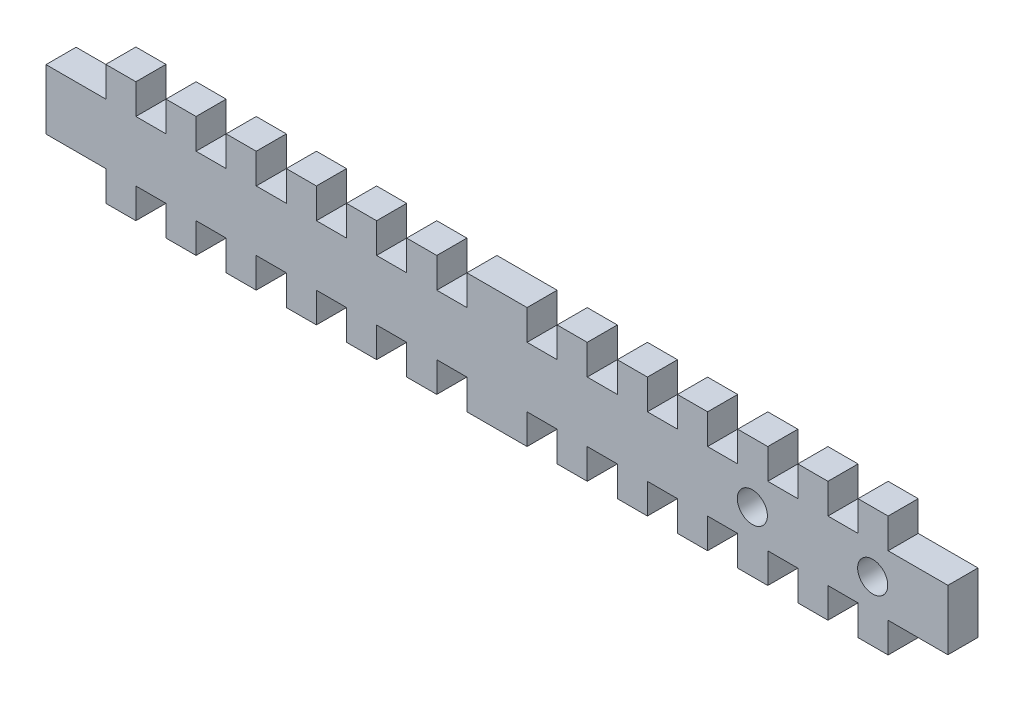
SolidWorks part; units mm, degrees
ref_plane "Front Plane" through (0, 0, 0) normal (0, 0, 1) x (1, 0, 0)
ref_plane "Top Plane" through (0, 0, 0) normal (0, 1, 0) x (1, 0, 0)
ref_plane "Right Plane" through (0, 0, 0) normal (1, 0, 0) x (0, 0, -1)
sketch "Sketch1" plane through (0, 0, 0) normal (0, 0, 1) x (1, 0, 0)
  line L0 (-95.25, 21.2167) -> (-82.55, 21.2167) construction
  line L1 (-82.55, 12.7) -> (-76.2, 12.7)
  line L2 (-95.1675, 6.35) -> (-95.1675, -6.35)
  line L3 (-82.55, -12.7) -> (-76.2, -12.7)
  line L4 (95.1675, 6.35) -> (95.1675, -6.35)
  line L5 (-95.25, 12.7) -> (95.25, -12.7) construction
  line L6 (-95.25, -12.7) -> (95.25, 12.7) construction
  line L7 (-82.55, 12.7) -> (-82.55, 6.35)
  line L8 (-82.55, 6.35) -> (-95.1675, 6.35)
  line L9 (0, 2.9169) -> (0, -2.0983) construction
  line L10 (-3.425, 0) -> (5.9529, 0) construction
  line L11 (-82.55, -6.35) -> (-95.1675, -6.35)
  line L12 (-82.55, -12.7) -> (-82.55, -6.35)
  line L13 (82.55, -12.7) -> (82.55, -6.35)
  line L14 (82.55, -6.35) -> (95.1675, -6.35)
  line L15 (82.55, 12.7) -> (82.55, 6.35)
  line L16 (82.55, 6.35) -> (95.1675, 6.35)
  line L17 (-82.55, -20.0623) -> (-76.2, -20.0623) construction
  line L18 (-76.2, -12.7) -> (-76.2, -6.35)
  line L19 (-69.85, 12.7) -> (-63.5, 12.7)
  line L20 (-57.15, 12.7) -> (-50.8, 12.7)
  line L21 (-76.2, 12.7) -> (-76.2, 6.35)
  line L22 (-63.5, 12.7) -> (-63.5, 6.35)
  line L23 (-69.85, 12.7) -> (-69.85, 6.35)
  line L24 (-50.8, 6.35) -> (-44.45, 6.35)
  line L25 (-50.8, 12.7) -> (-50.8, 6.35)
  line L26 (-57.15, 12.7) -> (-57.15, 6.35)
  line L27 (-38.1, 6.35) -> (-31.75, 6.35)
  line L28 (-38.1, 12.7) -> (-38.1, 6.35)
  line L29 (-44.45, 12.7) -> (-44.45, 6.35)
  line L30 (-25.4, 6.35) -> (-19.05, 6.35)
  line L31 (-25.4, 12.7) -> (-25.4, 6.35)
  line L32 (-31.75, 12.7) -> (-31.75, 6.35)
  line L33 (-12.7, 6.35) -> (-6.35, 6.35)
  line L34 (-12.7, 12.7) -> (-12.7, 6.35)
  line L35 (-19.05, 12.7) -> (-19.05, 6.35)
  line L36 (12.7, -6.35) -> (6.35, -6.35)
  line L37 (6.35, 12.7) -> (0, 12.7)
  line L38 (-6.35, 12.7) -> (-6.35, 6.35)
  line L39 (-6.35, -6.35) -> (-12.7, -6.35)
  line L40 (12.7, 12.7) -> (12.7, 6.35)
  line L41 (6.35, 12.7) -> (6.35, 6.35)
  line L42 (6.35, 6.35) -> (12.7, 6.35)
  line L43 (25.4, 12.7) -> (25.4, 6.35)
  line L44 (19.05, 12.7) -> (19.05, 6.35)
  line L45 (19.05, 6.35) -> (25.4, 6.35)
  line L46 (38.1, 12.7) -> (38.1, 6.35)
  line L47 (31.75, 12.7) -> (31.75, 6.35)
  line L48 (82.55, 6.35) -> (82.55, 12.7)
  line L49 (31.75, 6.35) -> (38.1, 6.35)
  line L50 (50.8, 12.7) -> (50.8, 6.35)
  line L51 (44.45, 12.7) -> (44.45, 6.35)
  line L52 (44.45, 6.35) -> (50.8, 6.35)
  line L53 (63.5, 12.7) -> (63.5, 6.35)
  line L54 (57.15, 12.7) -> (57.15, 6.35)
  line L55 (57.15, 6.35) -> (63.5, 6.35)
  line L56 (-19.05, 12.7) -> (-12.7, 12.7)
  line L57 (6.35, 12.7) -> (-6.35, 12.7)
  line L58 (76.2, 12.7) -> (76.2, 6.35)
  line L59 (-12.7, 12.7) -> (-19.05, 12.7)
  line L60 (-25.4, 12.7) -> (-31.75, 12.7)
  line L61 (-38.1, 12.7) -> (-44.45, 12.7)
  line L62 (31.75, 12.7) -> (25.4, 12.7)
  line L63 (44.45, 12.7) -> (38.1, 12.7)
  line L64 (57.15, 12.7) -> (50.8, 12.7)
  line L65 (69.85, 12.7) -> (63.5, 12.7)
  line L66 (69.85, 12.7) -> (69.85, 6.35)
  line L67 (69.85, 6.35) -> (76.2, 6.35)
  line L68 (-44.45, -6.35) -> (-50.8, -6.35)
  line L69 (-69.85, -12.7) -> (-69.85, -6.35)
  line L70 (-63.5, -12.7) -> (-63.5, -6.35)
  line L71 (-31.75, -6.35) -> (-38.1, -6.35)
  line L72 (-57.15, -12.7) -> (-57.15, -6.35)
  line L73 (-50.8, -12.7) -> (-50.8, -6.35)
  line L74 (95.1675, 0) -> (79.2925, 0) construction
  line L75 (79.2925, 0) -> (53.8925, 0) construction
  line L80 (-19.05, -6.35) -> (-25.4, -6.35)
  line L81 (-44.45, -12.7) -> (-44.45, -6.35)
  line L82 (-38.1, -12.7) -> (-38.1, -6.35)
  line L83 (-63.5, 6.35) -> (-57.15, 6.35)
  line L84 (-31.75, -12.7) -> (-31.75, -6.35)
  line L85 (-25.4, -12.7) -> (-25.4, -6.35)
  line L87 (-19.05, -12.7) -> (-19.05, -6.35)
  line L88 (-12.7, -12.7) -> (-12.7, -6.35)
  line L89 (-6.35, -12.7) -> (6.35, -12.7)
  line L90 (-6.35, -12.7) -> (-6.35, -6.35)
  line L91 (-57.15, -6.35) -> (-63.5, -6.35)
  line L92 (6.35, -6.35) -> (12.7, -6.35)
  line L93 (6.35, -12.7) -> (6.35, -6.35)
  line L94 (12.7, -12.7) -> (12.7, -6.35)
  line L95 (19.05, -6.35) -> (25.4, -6.35)
  line L96 (19.05, -12.7) -> (19.05, -6.35)
  line L97 (25.4, -12.7) -> (25.4, -6.35)
  line L98 (31.75, -6.35) -> (38.1, -6.35)
  line L99 (31.75, -12.7) -> (31.75, -6.35)
  line L100 (38.1, -12.7) -> (38.1, -6.35)
  line L101 (44.45, -6.35) -> (50.8, -6.35)
  line L102 (44.45, -12.7) -> (44.45, -6.35)
  line L103 (50.8, -12.7) -> (50.8, -6.35)
  line L104 (57.15, -6.35) -> (63.5, -6.35)
  line L105 (57.15, -12.7) -> (57.15, -6.35)
  line L106 (63.5, -12.7) -> (63.5, -6.35)
  line L107 (69.85, -6.35) -> (76.2, -6.35)
  line L108 (69.85, -12.7) -> (69.85, -6.35)
  line L109 (76.2, -12.7) -> (76.2, -6.35)
  line L110 (-76.2, 6.35) -> (-69.85, 6.35)
  line L111 (76.2, -6.35) -> (69.85, -6.35)
  line L112 (-63.5, 12.7) -> (-69.85, 12.7)
  line L113 (-44.45, 12.7) -> (-38.1, 12.7)
  line L114 (-50.8, 12.7) -> (-57.15, 12.7)
  line L115 (-50.8, 12.7) -> (-57.15, 12.7)
  line L116 (-38.1, 12.7) -> (-44.45, 12.7)
  line L117 (-31.75, 12.7) -> (-25.4, 12.7)
  line L118 (-38.1, 12.7) -> (-44.45, 12.7)
  line L119 (-25.4, 12.7) -> (-31.75, 12.7)
  line L120 (-25.4, 12.7) -> (-31.75, 12.7)
  line L121 (-19.05, 12.7) -> (-12.7, 12.7)
  line L122 (-12.7, 12.7) -> (-19.05, 12.7)
  line L123 (-6.35, 12.7) -> (6.35, 12.7)
  line L124 (0, 12.7) -> (0, 6.35) [skipped]
  line L125 (19.05, 6.35) -> (25.4, 6.35)
  line L126 (12.7, 12.7) -> (19.05, 12.7)
  line L127 (19.05, 12.7) -> (12.7, 12.7)
  line L128 (19.05, 12.7) -> (12.7, 12.7)
  line L129 (25.4, 12.7) -> (31.75, 12.7)
  line L130 (31.75, 12.7) -> (25.4, 12.7)
  line L131 (31.75, 12.7) -> (25.4, 12.7)
  line L132 (38.1, 12.7) -> (44.45, 12.7)
  line L133 (44.45, 12.7) -> (38.1, 12.7)
  line L134 (44.45, 12.7) -> (38.1, 12.7)
  line L135 (50.8, 12.7) -> (57.15, 12.7)
  line L136 (57.15, 12.7) -> (50.8, 12.7)
  line L137 (63.5, 12.7) -> (69.85, 12.7)
  line L138 (76.2, 12.7) -> (82.55, 12.7)
  line L139 (76.2, -12.7) -> (82.55, -12.7)
  line L140 (63.5, -12.7) -> (69.85, -12.7)
  line L141 (50.8, -12.7) -> (57.15, -12.7)
  line L142 (38.1, -12.7) -> (44.45, -12.7)
  line L143 (25.4, -12.7) -> (31.75, -12.7)
  line L144 (12.7, -12.7) -> (19.05, -12.7)
  line L145 (0, -12.7) -> (0, -6.35) [skipped]
  line L146 (-19.05, -12.7) -> (-12.7, -12.7)
  line L147 (-31.75, -12.7) -> (-25.4, -12.7)
  line L148 (-44.45, -12.7) -> (-38.1, -12.7)
  line L149 (-57.15, -12.7) -> (-50.8, -12.7)
  line L150 (-69.85, -12.7) -> (-63.5, -12.7)
  line L151 (-69.85, -6.35) -> (-76.2, -6.35)
  line L152 (25.4, -6.35) -> (19.05, -6.35)
  line L153 (31.75, 6.35) -> (38.1, 6.35)
  line L154 (44.45, 6.35) -> (50.8, 6.35)
  line L155 (38.1, -6.35) -> (31.75, -6.35)
  line L156 (57.15, 6.35) -> (63.5, 6.35)
  line L157 (50.8, -6.35) -> (44.45, -6.35)
  line L158 (63.5, -6.35) -> (57.15, -6.35)
  line L159 (69.85, 6.35) -> (76.2, 6.35)
  circle A0 centre (79.2925, 0) radius 3.175
  circle A1 centre (53.8925, 0) radius 3.175
  point P0 (0, 0)
  dimension "D2" = 6.35
  dimension "D3" = 6.35
  dimension "D1" = 15.875
extrude "Boss-Extrude1" add sketch "Sketch1" along normal blind 6.35 contours L151 L69 L150 L70 L91 L72 L149 L73 L68 L81 L148 L82 L71 L84 L147 L85 L80 L87 L146 L88 L39 L90 L89 L93 L36 L94 L144 L96 L95 L97 L143 L99 L98 L100 L142 L102 L101 L103 L141 L105 L104 L106 L140 L108 L107 L109 L139 L13 L14 L4 L16
